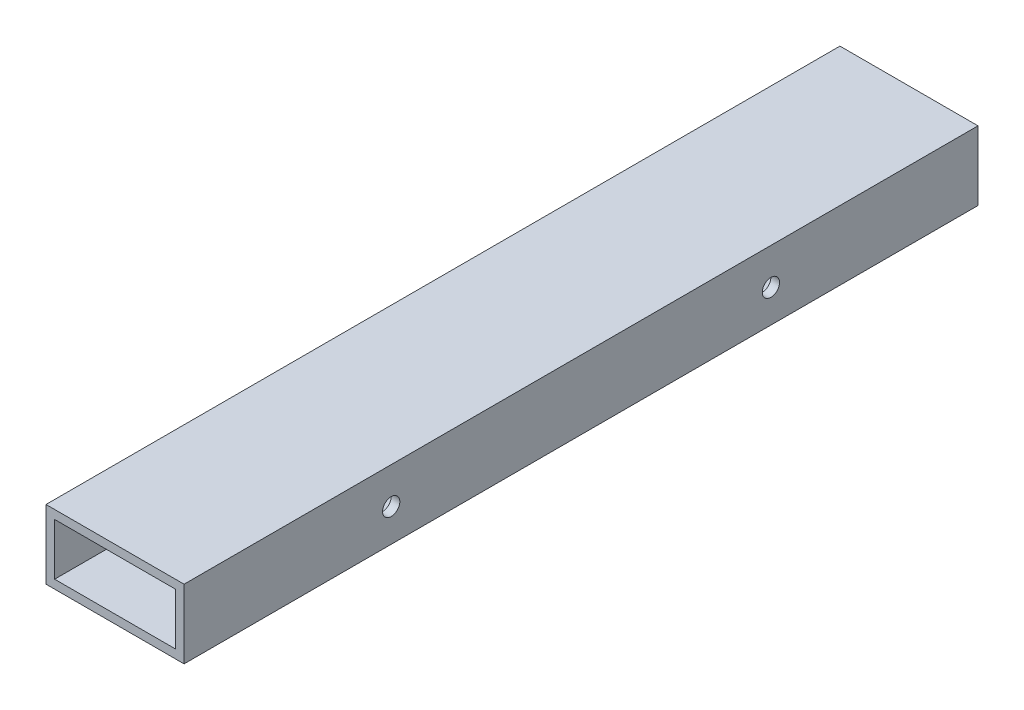
SolidWorks part; units mm, degrees
ref_plane "Front Plane" through (0, 0, 0) normal (0, 0, 1) x (1, 0, 0)
ref_plane "Top Plane" through (0, 0, 0) normal (0, 1, 0) x (1, 0, 0)
ref_plane "Right Plane" through (0, 0, 0) normal (1, 0, 0) x (0, 0, -1)
sketch "Sketch1" plane through (0, 0, 0) normal (0, 0, 1) x (1, 0, 0)
  line L0 (3.175, 22.225) -> (47.625, 22.225)
  line L1 (0, 0) -> (50.8, 0)
  line L2 (0, 0) -> (0, 25.4)
  line L3 (0, 25.4) -> (50.8, 25.4)
  line L4 (50.8, 0) -> (50.8, 25.4)
  line L5 (47.625, 3.175) -> (47.625, 22.225)
  line L6 (3.175, 3.175) -> (47.625, 3.175)
  line L7 (3.175, 3.175) -> (3.175, 22.225)
  dimension "D2" = 50.8
  dimension "D3" = 25.4
  dimension "D1" = 3.175
extrude "Boss-Extrude1" add sketch "Sketch1" along normal blind 292.1
sketch "Sketch2" plane through (50.8, 0, 0) normal (1, 0, 0) x (0, 0, -1)
  line L0 (-146.05, 25.4) -> (-146.05, 12.0268) construction
  line L1 (-292.1, 25.4) -> (0, 25.4) construction
  line L2 (-146.05, 12.0268) -> (-215.9, 12.0268) construction
  line L3 (-146.05, 12.0268) -> (-76.2, 12.0268) construction
  circle A0 centre (-215.9, 12.0268) radius 3.175
  circle A1 centre (-76.2, 12.0268) radius 3.175
  dimension "D3" = 6.35
  dimension "D1" = 13.3732
  dimension "D2" = 69.85
extrude "Cut-Extrude1" cut sketch "Sketch2" against normal through all both
